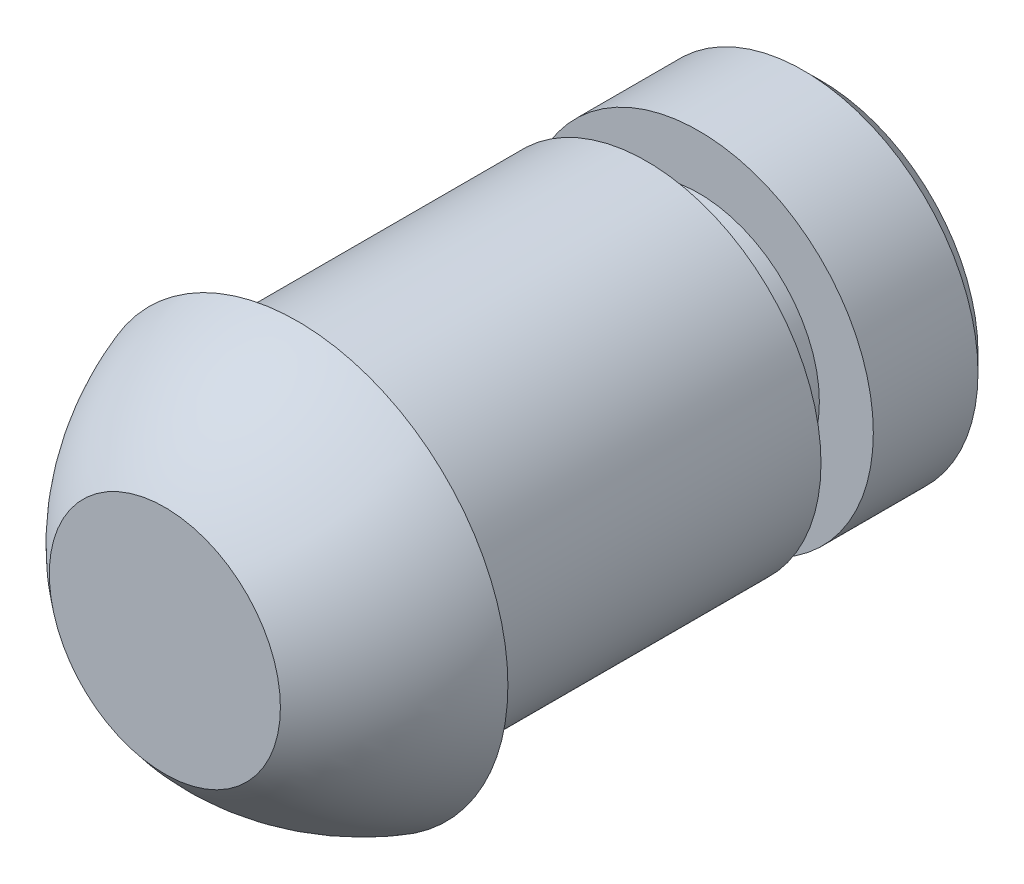
SolidWorks part; units mm, degrees
ref_plane "Front Plane" through (0, 0, 0) normal (0, 0, 1) x (1, 0, 0)
ref_plane "Top Plane" through (0, 0, 0) normal (0, 1, 0) x (1, 0, 0)
ref_plane "Right Plane" through (0, 0, 0) normal (1, 0, 0) x (0, 0, -1)
sketch "Sketch1" plane through (0, 0, 0) normal (1, 0, 0) x (0, 0, -1)
  line L0 (-1.8064, 0) -> (2.3585, 0)
  line L1 (-1.8457, 2) -> (2.1543, 2)
  line L2 (2.1543, 2) -> (2.1543, 1.3814)
  line L3 (2.1543, 1.3814) -> (2.7543, 1.3814)
  line L4 (2.7543, 1.3814) -> (2.7543, 2)
  line L5 (2.7543, 2) -> (4.1543, 2)
  line L6 (4.1543, 2) -> (4.1543, 0)
  line L7 (4.1543, 0) -> (2.3585, 0)
  line L8 (-1.8457, 2) -> (-1.8457, 2.4102)
  line L9 (-3.3686, 1.325) -> (-3.3686, 0)
  line L10 (-3.3686, 0) -> (-1.8064, 0)
  arc A0 (-1.8457, 2.4102) -> (-3.3686, 1.325) centre (-0.8255, -0.6325) ccw
  point P13 (-1.8026, 2.6952)
  point P15 (-4.0267, 0)
  point P16 (-3.3686, 0)
  point P17 (-1.8457, 2.4102)
  dimension "D1" = 4
  dimension "D2" = 0.6
  dimension "D3" = 2
  dimension "D4" = 1.325
  dimension "D5" = 1.4
revolve "Revolve1" add sketch "Sketch1" angle 360 about L0
chamfer "Chamfer1" distance 0.2 angle 45 1 edges at (2, 0, -4.1543)
